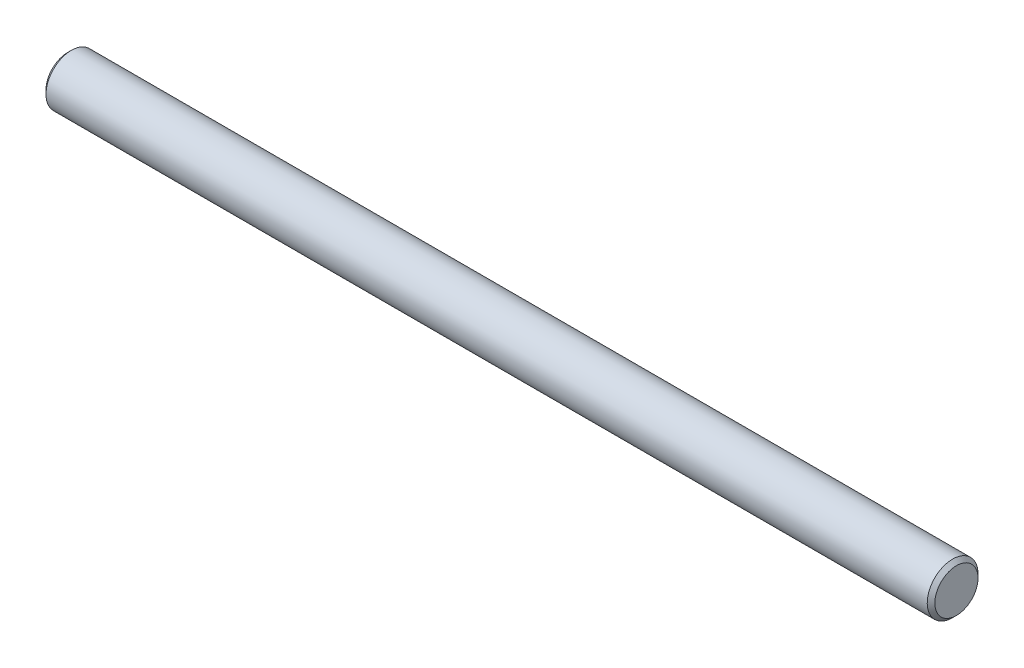
SolidWorks part; units mm, degrees
material "1.0420 (G200)"
ref_plane "Plan de face" through (0, 0, 0) normal (0, 0, 1) x (1, 0, 0)
ref_plane "Plan de dessus" through (0, 0, 0) normal (0, 1, 0) x (1, 0, 0)
ref_plane "Plan de droite" through (0, 0, 0) normal (1, 0, 0) x (0, 0, -1)
sketch "Esquisse1" plane through (0, 0, 0) normal (0, 0, 1) x (1, 0, 0)
  line L0 (0, 0) -> (-70, 0)
  line L1 (-70, 0) -> (-70, 1.7)
  line L2 (-70, 1.7) -> (-69.7, 2)
  line L3 (-69.7, 2) -> (-0.3, 2)
  line L4 (-0.3, 2) -> (0, 1.7)
  line L5 (0, 1.7) -> (0, 0)
  dimension "D1" = 0.3
  dimension "D2" = 0.3
  dimension "D3" = 0.3
  dimension "D4" = 0.3
  dimension "D5" = 70
  dimension "D6" = 2
revolve "Révolution1" add sketch "Esquisse1" angle 360 about L0
